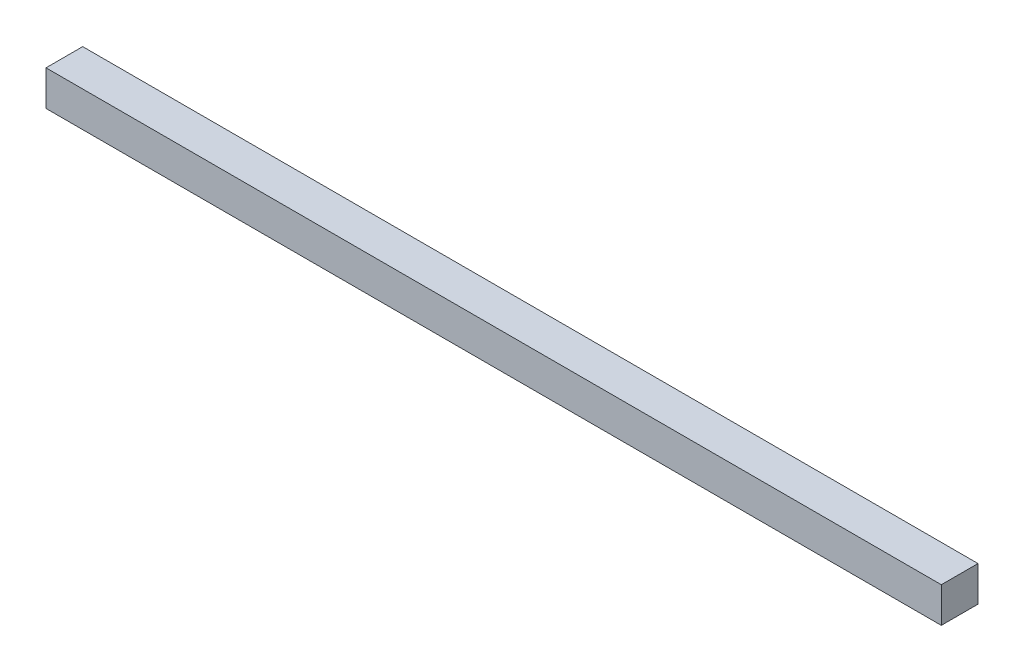
SolidWorks part; units mm, degrees
ref_plane "Front Plane" through (0, 0, 0) normal (0, 0, 1) x (1, 0, 0)
ref_plane "Top Plane" through (0, 0, 0) normal (0, 1, 0) x (1, 0, 0)
ref_plane "Right Plane" through (0, 0, 0) normal (1, 0, 0) x (0, 0, -1)
sketch "Sketch1" plane through (0, 0, 0) normal (0, 1, 0) x (1, 0, 0)
  line L1 (-152.5, -125) -> (152.5, -125)
  line L2 (-152.5, -125) -> (-152.5, 125)
  line L3 (-152.5, 125) -> (152.5, 125)
  line L4 (152.5, -125) -> (152.5, 125)
  line L5 (-152.5, -125) -> (152.5, 125) construction
  line L6 (-152.5, 125) -> (152.5, -125) construction
  line L7 (-165, -137.5) -> (165, -137.5)
  line L8 (-165, -137.5) -> (-165, 137.5)
  line L9 (-165, 137.5) -> (165, 137.5)
  line L10 (165, -137.5) -> (165, 137.5)
  line L11 (-165, -137.5) -> (165, 137.5) construction
  line L12 (-165, 137.5) -> (165, -137.5) construction
  point P0 (0, 0)
  point P5 (0, 0)
extrude "Boss-Extrude4" add sketch "Sketch1" along normal blind 12
sketch "Sketch2" plane through (165, 0, 0) normal (1, 0, 0) x (0, 0, -1)
  line L0 (0, 12) -> (0, 152) construction
  line L1 (-137.5, 12) -> (137.5, 12) construction
  line L2 (0, 152) -> (-137.5, 12)
  line L3 (-137.5, 12) -> (-127.5, 12)
  line L4 (-127.5, 12) -> (0, 141.8182)
  line L5 (0, 152) -> (137.5, 12)
  line L6 (137.5, 12) -> (127.5, 12)
  line L7 (0, 141.8182) -> (127.5, 12)
extrude "Boss-Extrude6" add sketch "Sketch2" against normal up to surface (12.5 mm away) up to face at (152.5, 6, 0)
sketch "Sketch5" plane through (-165, 0, 0) normal (-1, 0, 0) x (0, 0, 1)
  line L0 (0, 12) -> (0, 152) construction
  line L1 (-137.5, 12) -> (137.5, 12) construction
  line L2 (0, 152) -> (-137.5, 12)
  line L3 (-137.5, 12) -> (-127.5, 12)
  line L4 (-127.5, 12) -> (0, 141.8182)
  line L5 (0, 152) -> (137.5, 12)
  line L6 (137.5, 12) -> (127.5, 12)
  line L7 (127.5, 12) -> (0, 141.8182)
extrude "Boss-Extrude7" add sketch "Sketch5" against normal up to surface (12.5 mm away) up to face at (-152.5, 6, 0)
sketch "Sketch6" plane through (152.5, 0, 0) normal (-1, 0, 0) x (0, 0, 1)
  line L0 (0, 152) -> (0, 141.8182) construction
  circle A0 centre (0, 146.9091) radius 11
  circle A1 centre (0, 146.9091) radius 15
extrude "Boss-Extrude8" add sketch "Sketch6" against normal up to surface (12.5 mm away) up to face at (165, 55.2727, 0)
sketch "Sketch7" plane through (152.5, 0, 0) normal (-1, 0, 0) x (0, 0, 1)
  line L0 (0, 152) -> (0, 141.8182) construction
  circle A0 centre (0, 146.9091) radius 11
extrude "Cut-Extrude2" cut sketch "Sketch7" against normal through all
sketch "Sketch8" plane through (0, 69.6316, 70.8976) normal (0, -0.7007, -0.7134) x (-1, 0, 0)
  line L0 (152.5, 101.1799) -> (152.5, -80.7789) construction
  line L1 (152.5, -80.7789) -> (-152.5, -80.7789) construction
  line L2 (-152.5, -80.7789) -> (0, -80.7789) construction
  line L3 (0, -80.7789) -> (0, 71.6699) construction
  line L4 (165, 101.1799) -> (165, -80.7789) construction
  line L5 (140, 15.2005) -> (165, 15.2005)
  line L6 (140, 15.2005) -> (140, 5.2005)
  line L7 (140, 5.2005) -> (165, 5.2005)
  line L8 (165, 15.2005) -> (165, 5.2005)
  line L9 (140, 15.2005) -> (165, 5.2005) construction
  line L10 (140, 5.2005) -> (165, 15.2005) construction
  line L11 (152.5, 15.2005) -> (152.5, 5.2005)
  line L12 (-140, 5.2005) -> (-165, 5.2005)
  line L13 (-165, 15.2005) -> (-165, 5.2005)
  line L14 (-140, 15.2005) -> (-165, 15.2005)
  line L15 (-140, 15.2005) -> (-140, 5.2005)
  line L16 (-152.5, 15.2005) -> (-152.5, 5.2005)
  point P4 (152.5, 10.2005)
  line M7 (152.5, 101.1799) -> (152.5, -80.7789)
  line M9 (165, -80.7789) -> (165, 101.1799)
extrude "Boss-Extrude9" add sketch "Sketch8" along normal up to surface (87.5427 mm away) contours L16 L14 L13 L12 | L7 L5 M7 M9
sketch "Sketch9" plane through (0, 69.6316, -70.8976) normal (0, -0.7007, 0.7134) x (1, 0, 0)
  line L0 (-152.5, 101.1799) -> (-152.5, -80.7789) construction
  line L1 (-152.5, -80.7789) -> (152.5, -80.7789) construction
  line L2 (152.5, -80.7789) -> (0, -80.7789) construction
  line L3 (0, -80.7789) -> (0, 71.5896) construction
  line L4 (-165, -80.7789) -> (-165, 101.1799) construction
  line L5 (-140, 5.2005) -> (-165, 5.2005)
  line L6 (-140, 5.2005) -> (-140, 15.2005)
  line L7 (-140, 15.2005) -> (-165, 15.2005)
  line L8 (-165, 5.2005) -> (-165, 15.2005)
  line L9 (-140, 5.2005) -> (-165, 15.2005) construction
  line L10 (-140, 15.2005) -> (-165, 5.2005) construction
  line L11 (-152.5, 5.2005) -> (-152.5, 15.2005)
  line L12 (140, 15.2005) -> (165, 15.2005)
  line L13 (165, 5.2005) -> (165, 15.2005)
  line L14 (140, 5.2005) -> (165, 5.2005)
  line L15 (140, 5.2005) -> (140, 15.2005)
  line L16 (152.5, 5.2005) -> (152.5, 15.2005)
  point P9 (-152.5, 10.2005)
  line M7 (-152.5, -80.7789) -> (-152.5, 101.1799)
  line M9 (-165, 101.1799) -> (-165, -80.7789)
extrude "Boss-Extrude10" add sketch "Sketch9" along normal up to surface (87.5427 mm away) contours L7 L5 M7 M9 | L16 L14 L13 L12
sketch "Sketch10" plane through (-152.5, 0, 0) normal (1, 0, 0) x (0, 0, -1)
  line L0 (0, 152) -> (0, 141.8182) construction
  line L2 (-12.5, 134.4091) -> (12.5, 134.4091)
  line L3 (-12.5, 134.4091) -> (-12.5, 159.4091)
  line L4 (-12.5, 159.4091) -> (12.5, 159.4091)
  line L5 (12.5, 134.4091) -> (12.5, 159.4091)
  line L6 (-12.5, 134.4091) -> (12.5, 159.4091) construction
  line L7 (-12.5, 159.4091) -> (12.5, 134.4091) construction
  point P4 (0, 146.9091)
extrude "Boss-Extrude11" add sketch "Sketch10" against normal up to surface (12.5 mm away) up to face at (-165, 27.9098, 52.841)
sketch "Sketch11" plane through (0, 0, 0) normal (0, 0, 1) x (1, 0, 0)
  line L0 (152.5, 157.9091) -> (152.5, 135.9091) construction
  line L1 (152.5, 161.9091) -> (146.5169, 161.9091)
  line L2 (152.5, 161.9091) -> (152.5, 157.9091)
  line L3 (152.5, 157.9091) -> (146.5169, 157.9091)
  line L4 (146.5169, 161.9091) -> (146.5169, 157.9091)
  line L5 (152.5, 146.9091) -> (128.8664, 146.9091) construction
  circle A0 centre (149.5084, 163.7989) radius 3.5385
revolve "Revolve1" add sketch "Sketch11" angle 360 about L5
sketch "Sketch12" plane through (165, 0, 0) normal (1, 0, 0) x (0, 0, -1)
  line L1 (-137.5, 0) -> (225.6832, 0)
  line L2 (-137.5, 0) -> (-137.5, 208.9724)
  line L3 (-137.5, 208.9724) -> (225.6832, 208.9724)
  line L4 (225.6832, 0) -> (225.6832, 208.9724)
extrude "Cut-Extrude4" cut sketch "Sketch12" against normal blind 12.5
sketch "Sketch13" plane through (152.5, 0, 0) normal (1, 0, 0) x (0, 0, -1)
  line L1 (-37.4784, 220.5822) -> (51.3713, 220.5822)
  line L2 (-37.4784, 220.5822) -> (-37.4784, 18.1696)
  line L3 (-37.4784, 18.1696) -> (51.3713, 18.1696)
  line L4 (51.3713, 220.5822) -> (51.3713, 18.1696)
extrude "Cut-Extrude5" cut sketch "Sketch13" against normal blind 12.5
sketch "Sketch14" plane through (-165, 0, 0) normal (-1, 0, 0) x (0, 0, 1)
  line L1 (-137.5, 0) -> (207.2452, 0)
  line L2 (-137.5, 0) -> (-137.5, 211.8566)
  line L3 (-137.5, 211.8566) -> (207.2452, 211.8566)
  line L4 (207.2452, 0) -> (207.2452, 211.8566)
extrude "Cut-Extrude6" cut sketch "Sketch14" against normal blind 12.5
sketch "Sketch15" plane through (-152.5, 0, 0) normal (-1, 0, 0) x (0, 0, 1)
  line L1 (-251.8336, -41.1283) -> (-49.9736, -41.1283)
  line L2 (-251.8336, -41.1283) -> (-251.8336, 33.3674)
  line L3 (-251.8336, 33.3674) -> (-49.9736, 33.3674)
  line L4 (-49.9736, -41.1283) -> (-49.9736, 33.3674)
extrude "Cut-Extrude7" cut sketch "Sketch15" against normal blind 390.5
